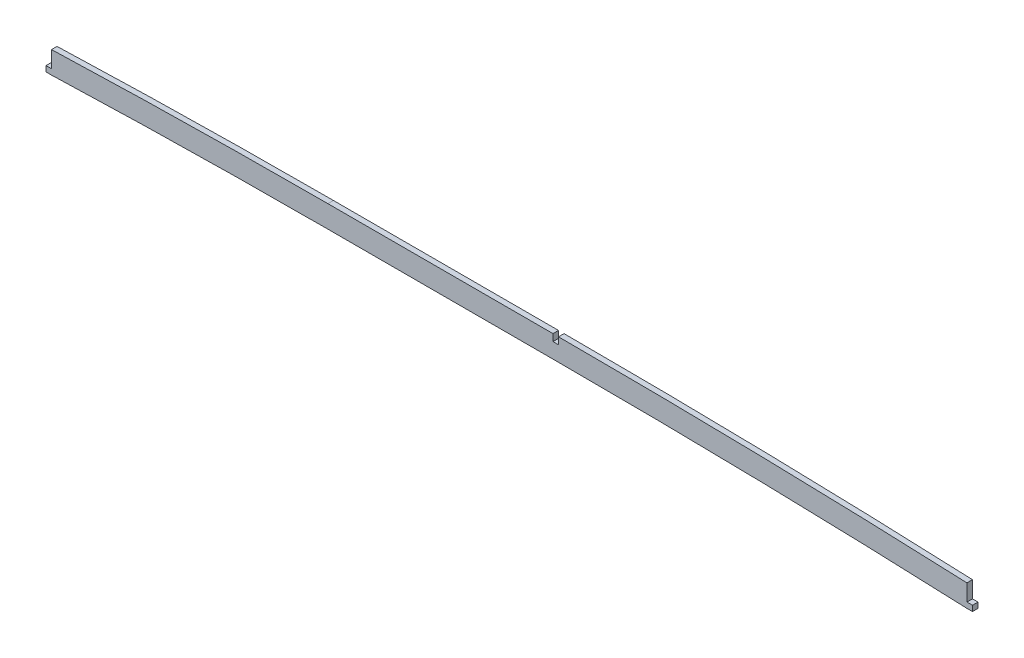
SolidWorks part; units mm, degrees
ref_plane "Front Plane" through (0, 0, 0) normal (0, 0, 1) x (1, 0, 0)
ref_plane "Top Plane" through (0, 0, 0) normal (0, 1, 0) x (1, 0, 0)
ref_plane "Right Plane" through (0, 0, 0) normal (1, 0, 0) x (0, 0, -1)
sketch "Sketch1" plane through (0, 0, 0) normal (0, 0, 1) x (1, 0, 0)
  line L0 (-875.6503, -406.8741) -> (-895.9703, -406.8741) construction
  line L1 (-477.5, 406.8741) -> (-60.1709, 406.8741) construction
  line L2 (-477.5, 381.4741) -> (-70.1709, 381.4741)
  line L3 (-2499.5, 265.5094) -> (-2495.9657, 240.3565)
  line L4 (2499.5, 261.9791) -> (2497.5242, 236.6561)
  line L5 (-477.5, 351.4706) -> (-477.5, -117.5) construction
  line L6 (1178.7584, 336.277) -> (1178.7584, -117.7475) construction
  line L7 (678.7584, 365.4102) -> (678.7584, 96.4743)
  line L8 (2539.3788, 258.8676) -> (2534.2912, 193.6628)
  line L9 (-477.5, 341.4741) -> (-60.1709, 341.4741)
  line L10 (-977.5, 332.8306) -> (-987.5, 332.8306)
  line L11 (-2539.1109, 259.9436) -> (-2530.003, 195.125) construction
  line L12 (-987.5, 332.8306) -> (-987.5, 342.8306)
  line L13 (-987.5, 342.8306) -> (-977.5, 342.8306)
  line L14 (678.7584, 325.3723) -> (688.7584, 325.3723)
  line L15 (688.7584, 325.3723) -> (688.7584, 335.3723)
  line L16 (688.7584, 335.3723) -> (678.7584, 335.3723)
  line L17 (1178.7584, 306.1704) -> (1178.7584, 336.277) construction
  line L18 (-977.5, 372.8545) -> (-977.5, 38.3658)
  line L19 (-60.1709, 381.4741) -> (-60.1709, 368.9741)
  line L20 (-60.1709, 368.9741) -> (-70.1709, 368.9741)
  line L21 (-477.5, 341.4741) -> (-60.1709, 341.4741) construction
  line L22 (-2539.1109, 259.9436) -> (-2530.003, 195.125) construction
  line L23 (-70.1709, 368.9741) -> (-70.1709, 381.4741)
  line L24 (-477.5, 381.4741) -> (-60.1709, 381.4741) construction
  arc A0 (1180.6092, 361.6095) -> (803.9292, 384.936) centre (-60.1709, -16621.7092) ccw construction
  arc A1 (803.9292, 384.936) -> (537.2292, 396.3918) centre (-60.1709, -16621.7092) ccw construction
  arc A2 (537.2292, 396.3918) -> (-60.1709, 406.8741) centre (-60.1709, -16621.7092) ccw construction
  arc A3 (-477.5, 406.8741) -> (-2499.5, 265.5094) centre (-477.5, -14124.5747) ccw construction
  arc A4 (1180.6092, 361.6095) -> (2499.5, 261.9791) centre (-18338.8038, -266812.5867) cw construction
  arc A5 (1178.7584, 336.277) -> (2497.5242, 236.6561) centre (-18338.8038, -266812.5867) cw
  arc A7 (799.4527, 359.7304) -> (536.3381, 371.0075) centre (-60.1709, -16621.7092) ccw
  arc A8 (536.3381, 371.0075) -> (-60.1709, 381.4741) centre (-60.1709, -16621.7092) ccw
  arc A9 (-477.5, 381.4741) -> (-2495.9657, 240.3565) centre (-477.5, -14124.5747) ccw
  arc A10 (678.7584, 325.3723) -> (534.9348, 331.0321) centre (-60.1709, -16621.7092) ccw
  arc A11 (534.9348, 331.0321) -> (-60.1709, 341.4741) centre (-60.1709, -16621.7092) ccw
  arc A12 (-477.5, 341.4741) -> (-977.5, 332.8306) centre (-477.5, -14124.5747) ccw
  arc A13 (-477.5, 341.4741) -> (-2530.003, 195.125) centre (-477.5, -14124.5747) ccw construction
  arc A14 (797.4304, 319.7815) -> (534.9348, 331.0321) centre (-60.1709, -16621.7092) ccw construction
  arc A18 (-477.5, 341.4741) -> (-2530.003, 195.125) centre (-477.5, -14124.5747) ccw construction
  arc A19 (1175.8438, 296.3834) -> (2534.2912, 193.6628) centre (-18338.8038, -266812.5867) cw construction
  arc A21 (1175.8438, 296.3834) -> (797.4304, 319.7815) centre (-60.1709, -16621.7092) ccw construction
  arc A23 (797.4304, 319.7815) -> (534.9348, 331.0321) centre (-60.1709, -16621.7092) ccw construction
  arc A25 (534.9348, 331.0321) -> (-60.1709, 341.4741) centre (-60.1709, -16621.7092) ccw construction
  arc A26 (1178.7584, 336.277) -> (799.4527, 359.7304) centre (-60.1709, -16621.7092) ccw construction
  dimension "D1" = 14531.4488
  dimension "D2" = 267886.2793
  dimension "D3" = 17028.5833
  dimension "D4" = 17028.5833
  dimension "D5" = 417.3291
  dimension "D6" = 4999
  dimension "D7" = 2022
  dimension "D8" = 1318.8908
  dimension "D9" = 1658.1092
  dimension "D11" = 40
  dimension "D12" = 40
  dimension "D13" = 10
  dimension "D14" = 10
  dimension "D15" = 10
  dimension "D16" = 500
  dimension "D10" = 500
  dimension "D17" = 10
  dimension "D18" = 10
  dimension "D19" = 12.5
extrude "Boss-Extrude1" add sketch "Sketch1" along normal blind 10
